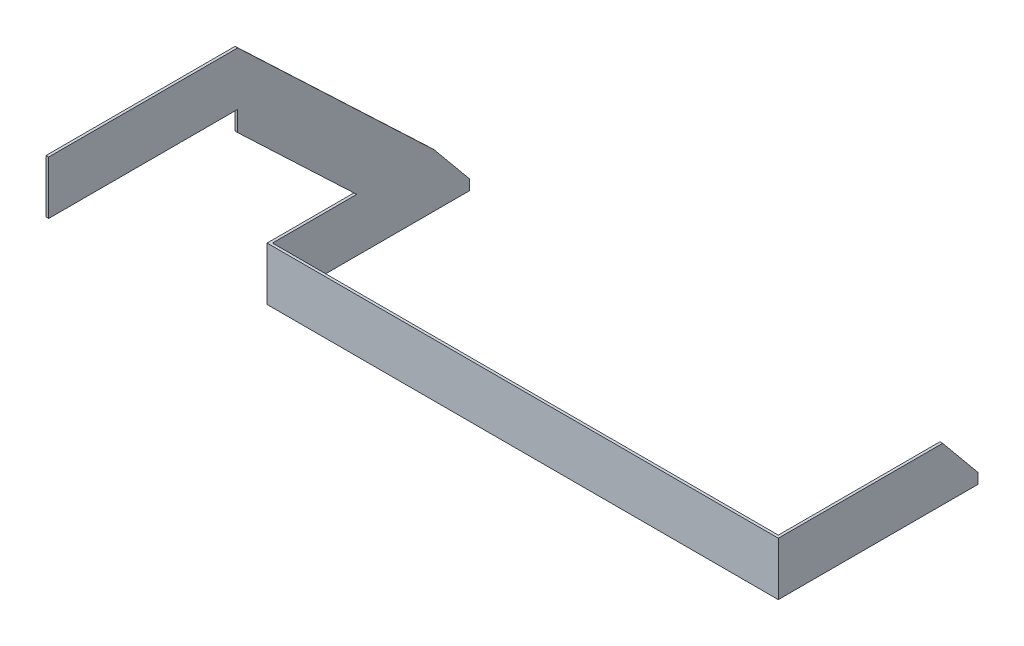
SolidWorks part; units mm, degrees
ref_plane "Alzado" through (0, 0, 0) normal (0, 0, 1) x (1, 0, 0)
ref_plane "Planta" through (0, 0, 0) normal (0, 1, 0) x (1, 0, 0)
ref_plane "Vista lateral" through (0, 0, 0) normal (1, 0, 0) x (0, 0, -1)
sketch "Croquis1" plane through (0, 0, 0) normal (0, 1, 0) x (1, 0, 0)
  line L1 (-96, 0.5) -> (96, 0.5)
  line L2 (-96, 0.5) -> (-96, -0.5)
  line L3 (-96, -0.5) -> (96, -0.5)
  line L4 (96, 0.5) -> (96, -0.5)
  line L5 (-96, 0.5) -> (96, -0.5) construction
  line L6 (-96, -0.5) -> (96, 0.5) construction
  line L7 (-96, -0.5) -> (-95, -0.5)
  line L8 (-96, -0.5) -> (-96, 74.5)
  line L9 (-96, 74.5) -> (-95, 74.5)
  line L10 (-95, -0.5) -> (-95, 74.5)
  line L11 (96, -0.5) -> (95, -0.5)
  line L12 (96, -0.5) -> (96, 74.5)
  line L13 (96, 74.5) -> (95, 74.5)
  line L14 (95, -0.5) -> (95, 74.5)
  point P0 (0, 0)
  dimension "D1" = 192
  dimension "D2" = 1
  dimension "D3" = 75
  dimension "D4" = 75
  dimension "D5" = 1
  dimension "D6" = 1
extrude "Saliente-Extruir1" add sketch "Croquis1" along normal blind 20 contours L1 L10 L9 L8 | L3 L10 L1 L2 | L3 L14 L1 L10 | L14 L1 L12 L13 | L14 L3 L4 L1
sketch "Croquis2" plane through (-96, 0, 0) normal (-1, 0, 0) x (0, 0, 1)
  line L6 (-74.5, 0) -> (-74.5, 7.3975)
  line L7 (-74.5, 20) -> (-74.5, 0) construction
  line L8 (-74.5, 7.3975) -> (12.5449, 90)
  line L9 (12.5449, 90) -> (12.5449, 62.428)
  line L10 (12.5449, 62.428) -> (-60.7329, -7.11)
  line L11 (-60.7329, -7.11) -> (-74.5, 7.3975)
  line L12 (0.5, 0) -> (-74.5, 0) construction
  line M3 (-74.5, 0) -> (0.5, 0)
  line M5 (0.5, 20) -> (-74.5, 20)
  dimension "D1" = 120
  dimension "D2" = 20
  dimension "D3" = 43.5
  dimension "D4" = 90
extrude "Saliente-Extruir2" add sketch "Croquis2" against normal blind 1 contours L10 L9 L8 M5 | L11 L10 L8 M3 M5
sketch "Croquis3" plane through (-96, 0, 0) normal (-1, 0, 0) x (0, 0, 1)
  line L0 (-61.2197, 20) -> (-74.5, 3.8924)
  line L1 (-74.5, 20) -> (-74.5, 0) construction
  line L2 (-74.5, 3.8924) -> (-74.5, 20)
  line L3 (-74.5, 20) -> (-61.2197, 20)
extrude "Cortar-Extruir1" cut sketch "Croquis3" against normal through all
sketch "Croquis4" plane through (-96, 0, 0) normal (-1, 0, 0) x (0, 0, 1)
  line L0 (12.5449, 90) -> (12.5449, 62.428) construction
  line L1 (12.5449, 90) -> (83.5449, 90)
  line L2 (12.5449, 90) -> (12.5449, 70)
  line L3 (12.5449, 70) -> (83.5449, 70)
  line L4 (83.5449, 90) -> (83.5449, 70)
  dimension "D1" = 20
  dimension "D2" = 0
  dimension "D3" = 71
extrude "Saliente-Extruir3" add sketch "Croquis4" against normal blind 1
